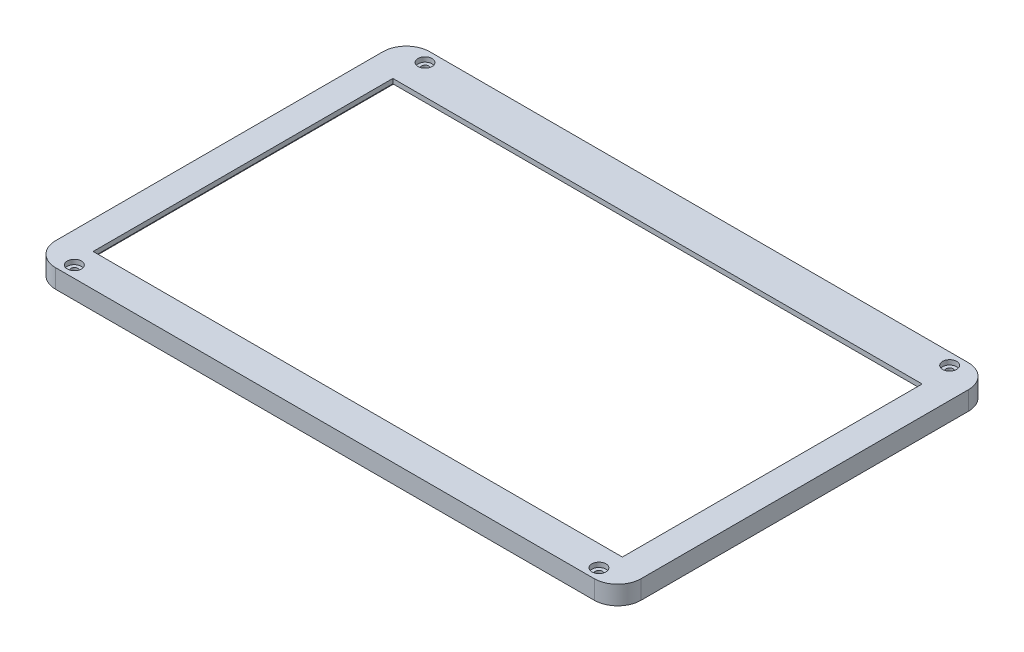
SolidWorks part; units mm, degrees
ref_plane "前视基准面" through (0, 0, 0) normal (0, 0, 1) x (1, 0, 0)
ref_plane "上视基准面" through (0, 0, 0) normal (0, 1, 0) x (1, 0, 0)
ref_plane "右视基准面" through (0, 0, 0) normal (1, 0, 0) x (0, 0, -1)
sketch "草图1" plane through (0, 0, 0) normal (0, 1, 0) x (1, 0, 0)
  line L1 (-99.3407, 63.102) -> (150.6593, 63.102)
  line L2 (-99.3407, 63.102) -> (-99.3407, -92.898)
  line L3 (-99.3407, -92.898) -> (150.6593, -92.898)
  line L4 (150.6593, 63.102) -> (150.6593, -92.898)
  line L5 (-87.3407, 49.102) -> (138.6593, 49.102)
  line L6 (-87.3407, 49.102) -> (-87.3407, -78.898)
  line L7 (-90.3407, 52.102) -> (143.6593, 52.102) construction
  line L8 (-90.3407, 52.102) -> (-90.3407, -85.898) construction
  line L9 (-90.3407, -85.898) -> (143.6593, -85.898) construction
  line L10 (143.6593, 52.102) -> (143.6593, -85.898) construction
  line L11 (-87.3407, -78.898) -> (138.6593, -78.898)
  line L12 (138.6593, 49.102) -> (138.6593, -78.898)
  point P4 (18.2503, -8.9096)
  point P9 (19.2503, -5.5256)
  point P14 (25.6593, -14.898)
  dimension "D1" = 250
  dimension "D2" = 156
  dimension "D3" = 138
  dimension "D4" = 234
  dimension "D5" = 9
  dimension "D6" = 7
  dimension "D7" = 11
  dimension "D8" = 7
  dimension "D9" = 3
  dimension "D10" = 3
  dimension "D11" = 7
  dimension "D12" = 5
extrude "凸台-拉伸1" add sketch "草图1" along normal blind 8
sketch "草图2" plane through (0, 0, 0) normal (0, -1, 0) x (1, 0, 0)
  line L0 (-99.3407, -63.102) -> (-99.3407, 92.898) construction
  line L1 (-93.0907, 82.648) -> (142.4093, 82.648)
  line L2 (-93.0907, 82.648) -> (-93.0907, -56.852)
  line L3 (-93.0907, -56.852) -> (142.4093, -56.852)
  line L4 (142.4093, 82.648) -> (142.4093, -56.852)
  line L5 (-93.0907, 82.648) -> (142.4093, -56.852) construction
  line L6 (-93.0907, -56.852) -> (142.4093, 82.648) construction
  line L7 (-99.3407, 92.898) -> (150.6593, 92.898) construction
  line L13 (150.6593, 92.898) -> (150.6593, -63.102) construction
  line L14 (150.6593, -63.102) -> (-99.3407, -63.102) construction
  point P4 (24.6593, 12.898)
  dimension "D1" = 235.5
  dimension "D2" = 139.5
  dimension "D3" = 6.25
  dimension "D4" = 10.25
  dimension "D5" = 8.25
  dimension "D6" = 6.25
extrude "切除-拉伸3" cut sketch "草图2" against normal blind 6
sketch "草图11" plane through (0, 0, -63.102) normal (0, 0, -1) x (-1, 0, 0)
  line L0 (99.3407, 8) -> (99.3407, 0) construction
  line L1 (-150.6593, 8) -> (99.3407, 8)
  line L2 (-150.6593, 8) -> (-150.6593, 0)
  line L3 (-150.6593, 0) -> (99.3407, 0)
  line L4 (99.3407, 8) -> (99.3407, 0)
  line L5 (-150.6593, 8) -> (99.3407, 0) construction
  line L6 (-150.6593, 0) -> (99.3407, 8) construction
  point P4 (-25.6593, 4)
extrude "凸台-拉伸3" add sketch "草图11" along normal blind 3.75
sketch "草图12" plane through (0, 0, 0) normal (0, -1, 0) x (1, 0, 0)
  line L5 (-89.3407, 92.898) -> (-99.3407, 92.898)
  line L6 (-99.3407, 92.898) -> (-99.3407, 82.898)
  line L7 (-99.3407, -56.852) -> (-99.3407, -66.852)
  line L8 (-99.3407, -66.852) -> (-89.3407, -66.852)
  line L9 (140.6593, -66.852) -> (150.6593, -66.852)
  line L10 (150.6593, -66.852) -> (150.6593, -56.852)
  line L11 (150.6593, 82.898) -> (150.6593, 92.898)
  line L12 (150.6593, 92.898) -> (140.6593, 92.898)
  arc A0 (140.6593, 92.898) -> (150.6593, 82.898) centre (140.6593, 82.898) cw
  arc A1 (150.6593, -56.852) -> (140.6593, -66.852) centre (140.6593, -56.852) cw
  arc A2 (-89.3407, -66.852) -> (-99.3407, -56.852) centre (-89.3407, -56.852) cw
  arc A3 (-99.3407, 82.898) -> (-89.3407, 92.898) centre (-89.3407, 82.898) cw
  point P4 (25.6593, 13.023)
  dimension "D1" = 10
extrude "切除-拉伸4" cut sketch "草图12" against normal blind 10
sketch "草图13" plane through (0, 0, 0) normal (0, -1, 0) x (1, 0, 0)
  line L0 (-99.3407, -56.852) -> (-99.3407, 82.898) construction
  line L1 (-86.3407, 87.898) -> (137.6593, 87.898) construction
  line L2 (-86.3407, 87.898) -> (-86.3407, -61.852) construction
  line L3 (-86.3407, -61.852) -> (137.6593, -61.852) construction
  line L4 (137.6593, 87.898) -> (137.6593, -61.852) construction
  line L6 (150.6593, 82.898) -> (150.6593, -56.852) construction
  line L7 (-89.3407, 92.898) -> (140.6593, 92.898) construction
  line L8 (-93.0907, -56.852) -> (142.4093, -56.852) construction
  circle A0 centre (-86.3407, 87.898) radius 1.5
  circle A1 centre (137.6593, 87.898) radius 1.5
  circle A2 centre (137.6593, -61.852) radius 1.5
  circle A3 centre (-86.3407, -61.852) radius 1.5
  point P8 (0, 0)
  point P11 (27.5493, 12.6457)
  point P12 (0, 0)
  dimension "D1" = 13
  dimension "D2" = 13
  dimension "D3" = 5
  dimension "D4" = 5
extrude "切除-拉伸5" cut sketch "草图13" against normal blind 10
sketch "草图14" plane through (0, 8, 0) normal (0, 1, 0) x (1, 0, 0)
  circle A0 centre (-86.3407, 61.852) radius 3
  circle A1 centre (137.6593, 61.852) radius 3
  circle A2 centre (137.6593, -87.898) radius 3
  circle A3 centre (-86.3407, -87.898) radius 3
extrude "切除-拉伸6" cut sketch "草图14" against normal blind 2
